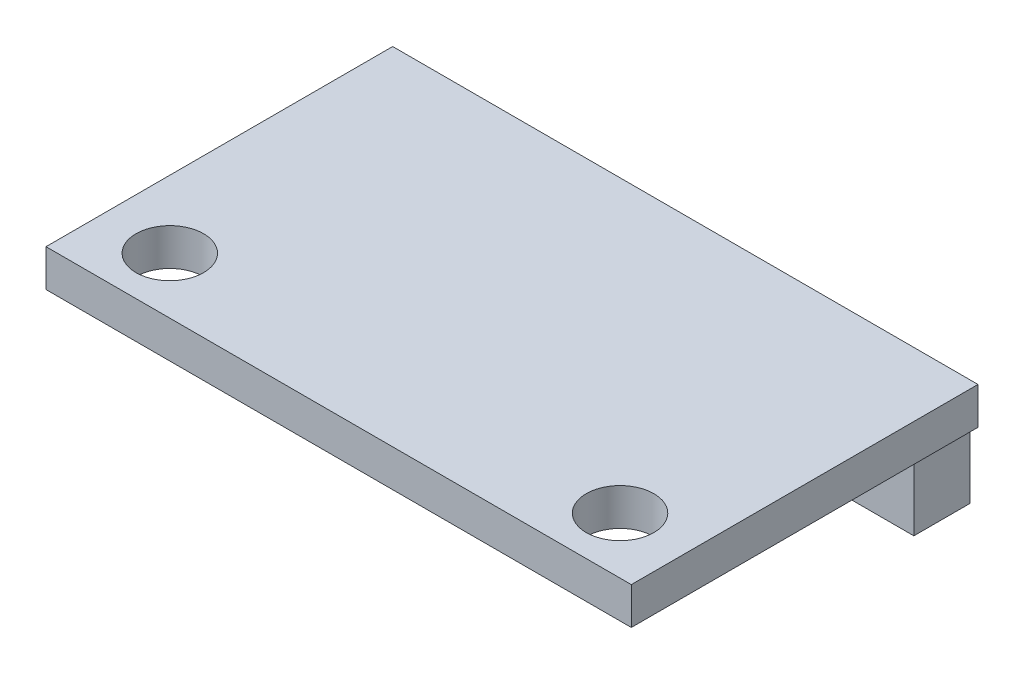
SolidWorks part; units mm, degrees
ref_plane "Front Plane" through (0, 0, 0) normal (0, 0, 1) x (1, 0, 0)
ref_plane "Top Plane" through (0, 0, 0) normal (0, 1, 0) x (1, 0, 0)
ref_plane "Right Plane" through (0, 0, 0) normal (1, 0, 0) x (0, 0, -1)
sketch "Sketch1" plane through (0, 0, 0) normal (0, 1, 0) x (1, 0, 0)
  line L1 (-13, -7.7) -> (13, -7.7)
  line L2 (-13, -7.7) -> (-13, 7.7)
  line L3 (-13, 7.7) -> (13, 7.7)
  line L4 (13, -7.7) -> (13, 7.7)
  line L5 (-13, -7.7) -> (13, 7.7) construction
  line L6 (-13, 7.7) -> (13, -7.7) construction
  circle A0 centre (-10, -5.2) radius 1.5
  circle A1 centre (10, -5.2) radius 1.5
  point P0 (0, 0)
  point P10 (0, 0)
  point P12 (9.1433, -5.7803)
  dimension "D3" = 3
  dimension "D1" = 26
  dimension "D2" = 15.4
  dimension "D4" = 20
  dimension "D5" = 2.5
  dimension "D6" = 3
extrude "Boss-Extrude1" add sketch "Sketch1" along normal blind 1.65
sketch "Sketch2" plane through (0, 0, 0) normal (0, -1, 0) x (1, 0, 0)
  line L0 (13, -7.7) -> (-13, -7.7) construction
  line L1 (-12.75, -5.1) -> (12.75, -5.1)
  line L2 (-12.75, -5.1) -> (-12.75, -7.6)
  line L3 (-12.75, -7.6) -> (12.75, -7.6)
  line L4 (12.75, -5.1) -> (12.75, -7.6)
  line L5 (13, 7.7) -> (13, -7.7) construction
  dimension "D1" = 2.5
  dimension "D2" = 25.5
  dimension "D3" = 0.1
  dimension "D4" = 0.25
extrude "Boss-Extrude2" add sketch "Sketch2" along normal blind 3
